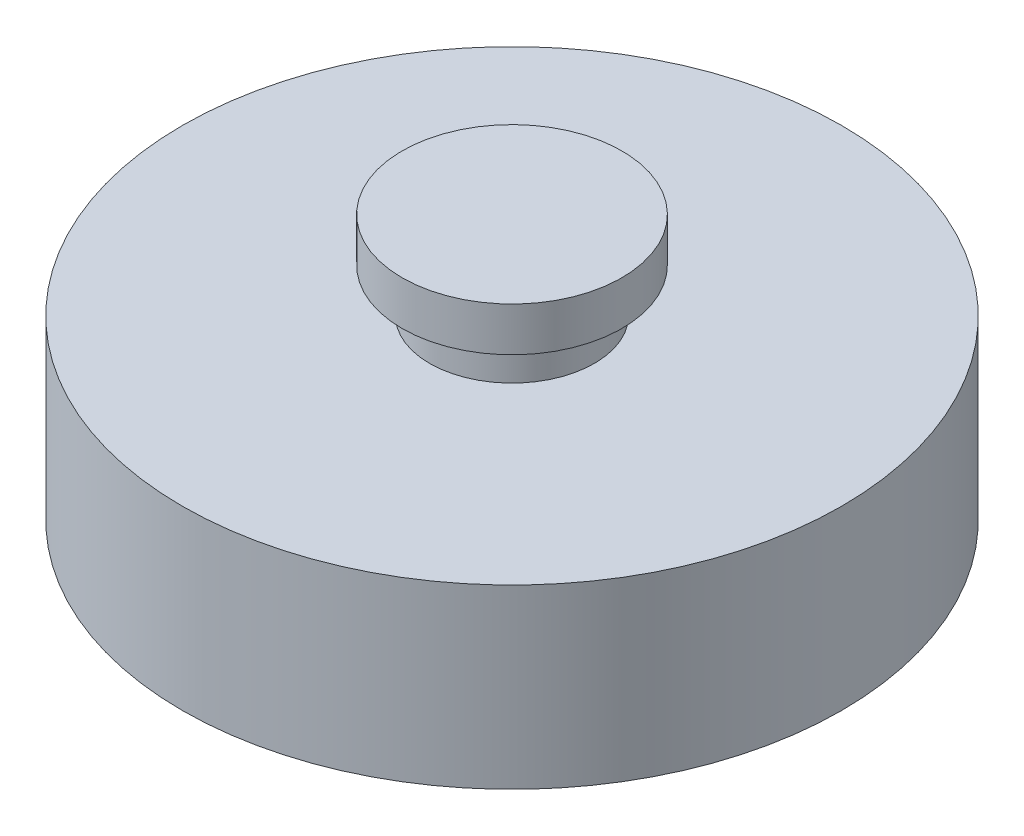
SolidWorks part; units mm, degrees
ref_plane "Front Plane" through (0, 0, 0) normal (0, 0, 1) x (1, 0, 0)
ref_plane "Top Plane" through (0, 0, 0) normal (0, 1, 0) x (1, 0, 0)
ref_plane "Right Plane" through (0, 0, 0) normal (1, 0, 0) x (0, 0, -1)
sketch "Sketch1" plane through (0, 0, 0) normal (0, 1, 0) x (1, 0, 0)
  circle A0 centre (0, 0) radius 300
extrude "Boss-Extrude1" add sketch "Sketch1" along normal blind 161 contours A0
sketch "Sketch2" plane through (0, 161, 0) normal (0, 1, 0) x (1, 0, 0)
  circle A0 centre (0, 0) radius 75
extrude "Boss-Extrude2" add sketch "Sketch2" along normal blind 40
sketch "Sketch3" plane through (0, 201, 0) normal (0, 1, 0) x (1, 0, 0)
  circle A0 centre (0, 0) radius 100
extrude "Boss-Extrude3" add sketch "Sketch3" along normal blind 40 contours A0
